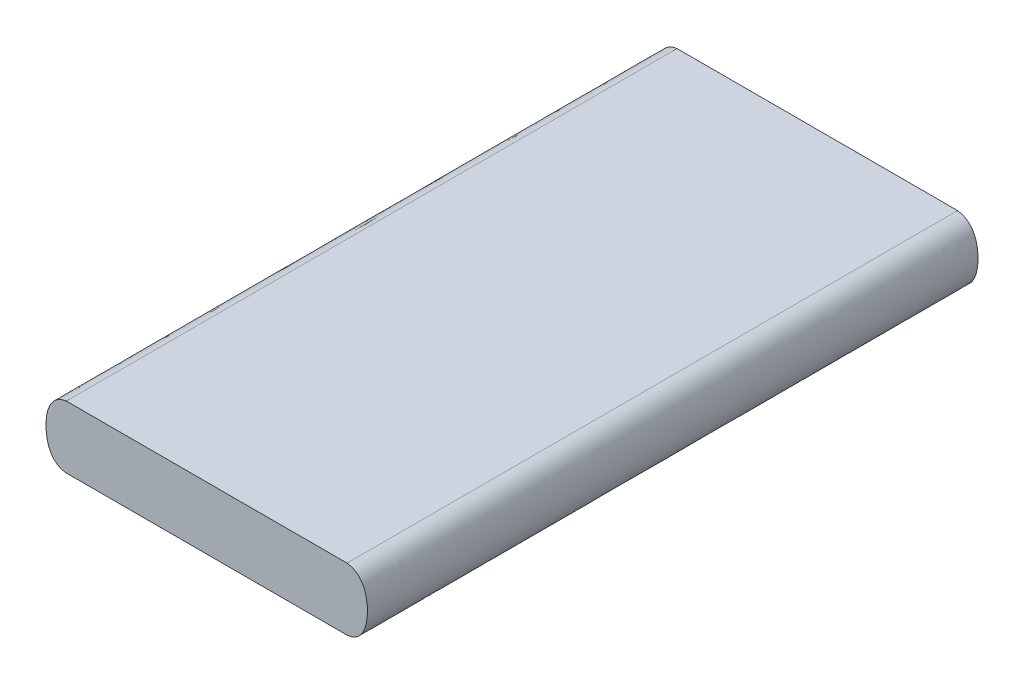
SolidWorks part; units mm, degrees
ref_plane "Front Plane" through (0, 0, 0) normal (0, 0, 1) x (1, 0, 0)
ref_plane "Top Plane" through (0, 0, 0) normal (0, 1, 0) x (1, 0, 0)
ref_plane "Right Plane" through (0, 0, 0) normal (1, 0, 0) x (0, 0, -1)
sketch "Sketch1" plane through (0, 0, 0) normal (0, 0, 1) x (1, 0, 0)
  line L1 (4.7429, 0) -> (70.0071, 0)
  line L3 (4.7429, 14.5) -> (70.0071, 14.5)
  spline S0 degree 3 poles (4.7429, 14.5) (1.2302, 14.0495) (-1.2298, 7.347) (1.2294, 0.2564) (4.7429, 0) knots 0 0 0 0 0.5 1 1 1 1
  spline S1 degree 3 poles (70.0071, 14.5) (73.5198, 14.0495) (75.9798, 7.347) (73.5206, 0.2564) (70.0071, 0) knots 0 0 0 0 0.5 1 1 1 1
  point P0 (0, 0)
  point P11 (0, 0)
extrude "Boss-Extrude1" add sketch "Sketch1" along normal blind 142
